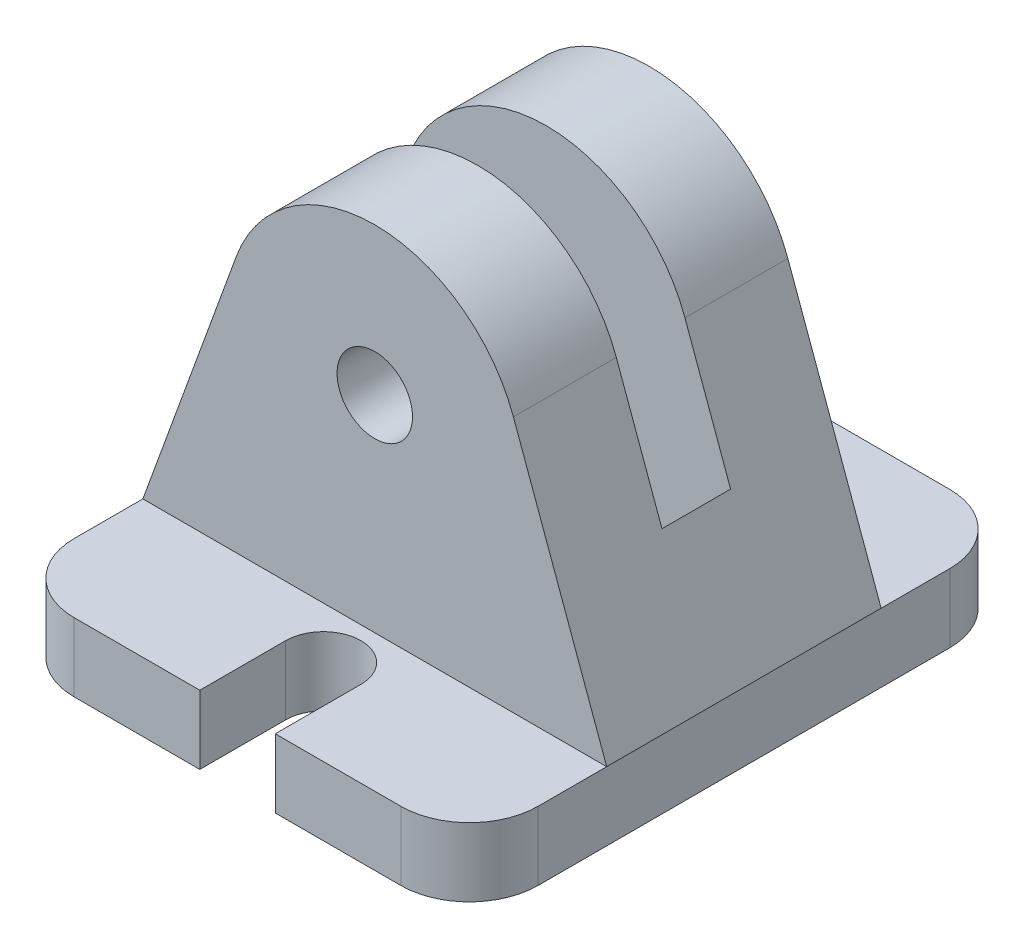
SolidWorks part; units mm, degrees
ref_plane "Front Plane" through (0, 0, 0) normal (0, 0, 1) x (1, 0, 0)
ref_plane "Top Plane" through (0, 0, 0) normal (0, 1, 0) x (1, 0, 0)
ref_plane "Right Plane" through (0, 0, 0) normal (1, 0, 0) x (0, 0, -1)
sketch "Sketch1" plane through (0, 0, 0) normal (0, 0, 1) x (1, 0, 0)
  line L0 (-10.1017, 3.6767) -> (-16.8995, -15)
  line L1 (-16.8995, -15) -> (16.8995, -15)
  line L2 (16.8995, -15) -> (10.1017, 3.6767)
  line L3 (0, 0) -> (0, -8346.2782) construction
  arc A0 (10.1017, 3.6767) -> (-10.1017, 3.6767) centre (0, 0) ccw
  circle A1 centre (0, 0) radius 2.75
  dimension "D1" = 5.5
  dimension "D2" = 8
  dimension "D3" = 20
  dimension "D4" = 15
extrude "Boss-Extrude1" add sketch "Sketch1" along normal mid plane 20
sketch "Sketch2" plane through (0, 0, 0) normal (0, 0, 1) x (1, 0, 0)
  circle A0 centre (0, 0) radius 14.5
  dimension "D1" = 29
extrude "Cut-Extrude1" cut sketch "Sketch2" against normal mid plane 5
sketch "Sketch3" plane through (0, -15, 0) normal (0, -1, 0) x (1, 0, 0)
  line L0 (0, 0) -> (50000, 0) construction
  line L1 (-16.8995, 10) -> (16.8995, 10)
  line L2 (-16.8995, 10) -> (-16.8995, 15)
  line L3 (-11.8995, 20) -> (11.8995, 20)
  line L4 (16.8995, 10) -> (16.8995, 15)
  line L5 (16.8995, -10) -> (16.8995, -15)
  line L6 (-11.8995, -20) -> (11.8995, -20)
  line L7 (-16.8995, -10) -> (-16.8995, -15)
  line L8 (-16.8995, -10) -> (16.8995, -10)
  line L9 (16.8995, 10) -> (16.8995, -10) construction
  line L11 (-16.8995, 10) -> (16.8995, 10)
  line L12 (-16.8995, 10) -> (-16.8995, -10)
  line L13 (-16.8995, -10) -> (16.8995, -10)
  line L14 (16.8995, 10) -> (16.8995, -10)
  arc A0 (11.8995, 20) -> (16.8995, 15) centre (11.8995, 15) cw
  arc A1 (-16.8995, 15) -> (-11.8995, 20) centre (-11.8995, 15) cw
  arc A2 (-16.8995, -15) -> (-11.8995, -20) centre (-11.8995, -15) ccw
  arc A3 (11.8995, -20) -> (16.8995, -15) centre (11.8995, -15) ccw
  line M4 (-16.8995, -10) -> (16.8995, -10)
  line M5 (16.8995, -10) -> (16.8995, 10)
  line M6 (16.8995, 10) -> (-16.8995, 10)
  line M7 (-16.8995, 10) -> (-16.8995, -10)
  dimension "D1" = 5
  dimension "D2" = 10
extrude "Boss-Extrude2" add sketch "Sketch3" along normal blind 5 contours A1 L2 L4 A0 L3 M6 | L0 L14 M7 M6 | L0 L12 M4 M5 | L6 A3 L5 L7 A2 M4
sketch "Sketch4" plane through (0, -20, 0) normal (0, -1, 0) x (1, 0, 0)
  line L0 (-2.75, 20) -> (-2.75, 13.75)
  line L1 (-11.8995, 20) -> (11.8995, 20) construction
  line L2 (-2.75, 13.75) -> (2.75, 13.75) construction
  line L3 (2.75, 13.75) -> (2.75, 20)
  line L4 (0, 0) -> (0, -50000) construction
  line L5 (-16.8995, 10) -> (16.8995, 10) construction
  line L6 (0, 0) -> (50000, 0) construction
  line L7 (-2.75, 20) -> (2.75, 20)
  line L8 (-2.75, -20) -> (-2.75, -13.75)
  line L9 (2.75, -13.75) -> (2.75, -20)
  line L10 (-2.75, -20) -> (2.75, -20)
  arc A0 (-2.75, 13.75) -> (2.75, 13.75) centre (0, 13.75) ccw
  arc A1 (-2.75, -13.75) -> (2.75, -13.75) centre (0, -13.75) cw
  dimension "D1" = 5.5
  dimension "D2" = 3.75
extrude "Cut-Extrude5" cut sketch "Sketch4" against normal through all
